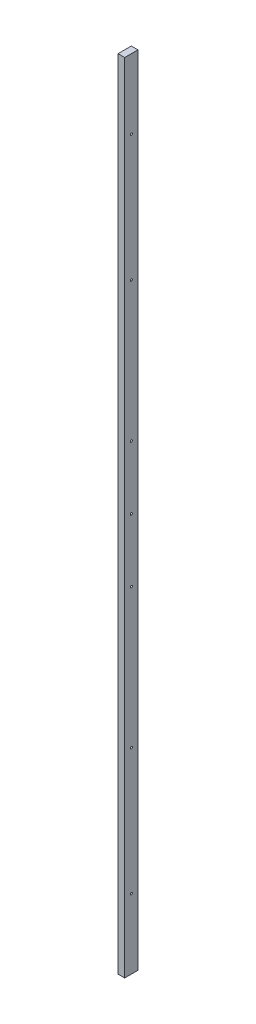
SolidWorks part; units mm, degrees
ref_plane "Спереди" through (0, 0, 0) normal (0, 0, 1) x (1, 0, 0)
ref_plane "Сверху" through (0, 0, 0) normal (0, 1, 0) x (1, 0, 0)
ref_plane "Справа" through (0, 0, 0) normal (1, 0, 0) x (0, 0, -1)
other "Configuration Table"
sketch "Эскиз1" plane through (0, 0, 0) normal (0, 1, 0) x (1, 0, 0)
  line L1 (12.5, 25) -> (-12.5, 25)
  line L2 (12.5, 25) -> (12.5, -25)
  line L3 (12.5, -25) -> (-12.5, -25)
  line L4 (-12.5, 25) -> (-12.5, -25)
  line L5 (12.5, 25) -> (-12.5, -25) construction
  line L6 (12.5, -25) -> (-12.5, 25) construction
  point P0 (0, 0)
extrude "Бобышка-Вытянуть1" add sketch "Эскиз1" along normal blind 3000
sketch "Эскиз2" plane through (12.5, 0, 0) normal (1, 0, 0) x (0, 0, -1)
  line L0 (0, 3000) -> (0, 2737.5) construction
  line L1 (-25, 3000) -> (25, 3000) construction
  line L2 (0, 0) -> (0, 262.5) construction
  line L3 (0, 262.5) -> (0, 737.5) construction
  circle A0 centre (0, 2737.5) radius 4
  circle A1 centre (0, 262.5) radius 4
  circle A2 centre (0, 737.5) radius 4
extrude "Вырез-Вытянуть1" cut sketch "Эскиз2" against normal blind 3000
sketch "Эскиз3" plane through (-12.5, 0, 0) normal (-1, 0, 0) x (0, 0, 1)
  line L0 (0, 2737.5) -> (0, 2262.5) construction
  circle A0 centre (0, 2262.5) radius 4
extrude "Вырез-Вытянуть2" cut sketch "Эскиз3" against normal blind 3000
sketch "Эскиз4" plane through (-12.5, 0, 0) normal (-1, 0, 0) x (0, 0, 1)
  line L0 (0, 2262.5) -> (0, 1737.5) construction
  line L1 (0, 737.5) -> (0, 1262.5) construction
  circle A0 centre (0, 1737.5) radius 4
  circle A1 centre (0, 1262.5) radius 4
extrude "Вырез-Вытянуть3" cut sketch "Эскиз4" against normal blind 3000
sketch "Эскиз5" plane through (-12.5, 0, 0) normal (-1, 0, 0) x (0, 0, 1)
  circle A0 centre (0, 1500) radius 4
extrude "Вырез-Вытянуть4" cut sketch "Эскиз5" against normal blind 50
